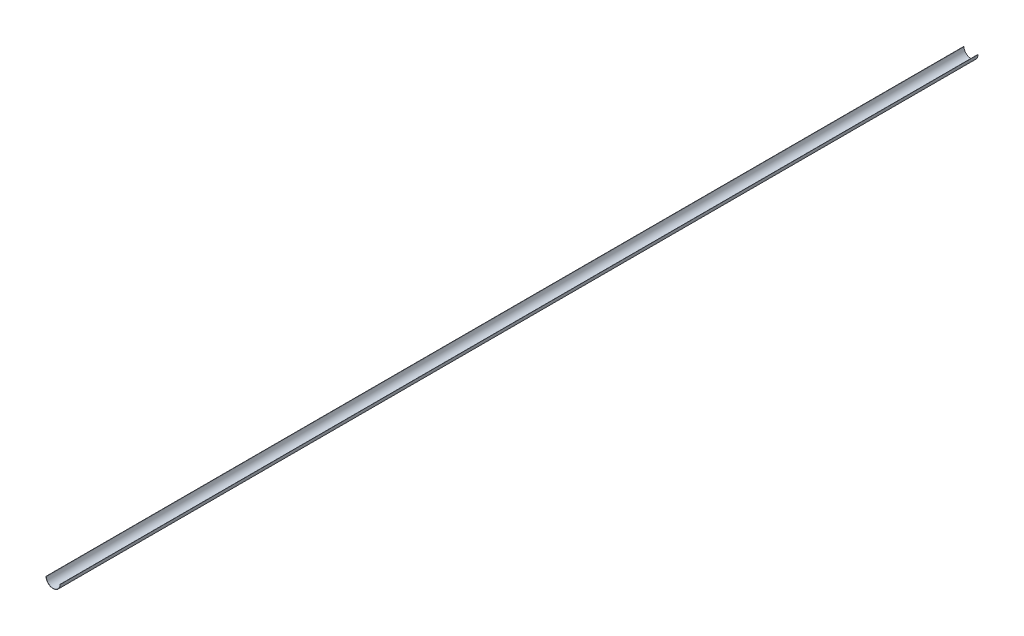
SolidWorks part; units mm, degrees
ref_plane "Front Plane" through (0, 0, 0) normal (0, 0, 1) x (1, 0, 0)
ref_plane "Top Plane" through (0, 0, 0) normal (0, 1, 0) x (1, 0, 0)
ref_plane "Right Plane" through (0, 0, 0) normal (1, 0, 0) x (0, 0, -1)
sketch "Sketch2" plane through (0, 0, 0) normal (0, 0, 1) x (1, 0, 0)
  line L0 (-7.75, 0) -> (-7.5, 0)
  line L1 (7.5, 0) -> (7.75, 0)
  arc A0 (-7.5, 0) -> (7.5, 0) centre (0, 0) ccw
  arc A1 (-7.75, 0) -> (7.75, 0) centre (0, 0) ccw
  dimension "D1" = 15
  dimension "D2" = 15.5
extrude "Boss-Extrude1" add sketch "Sketch2" along normal blind 1000
